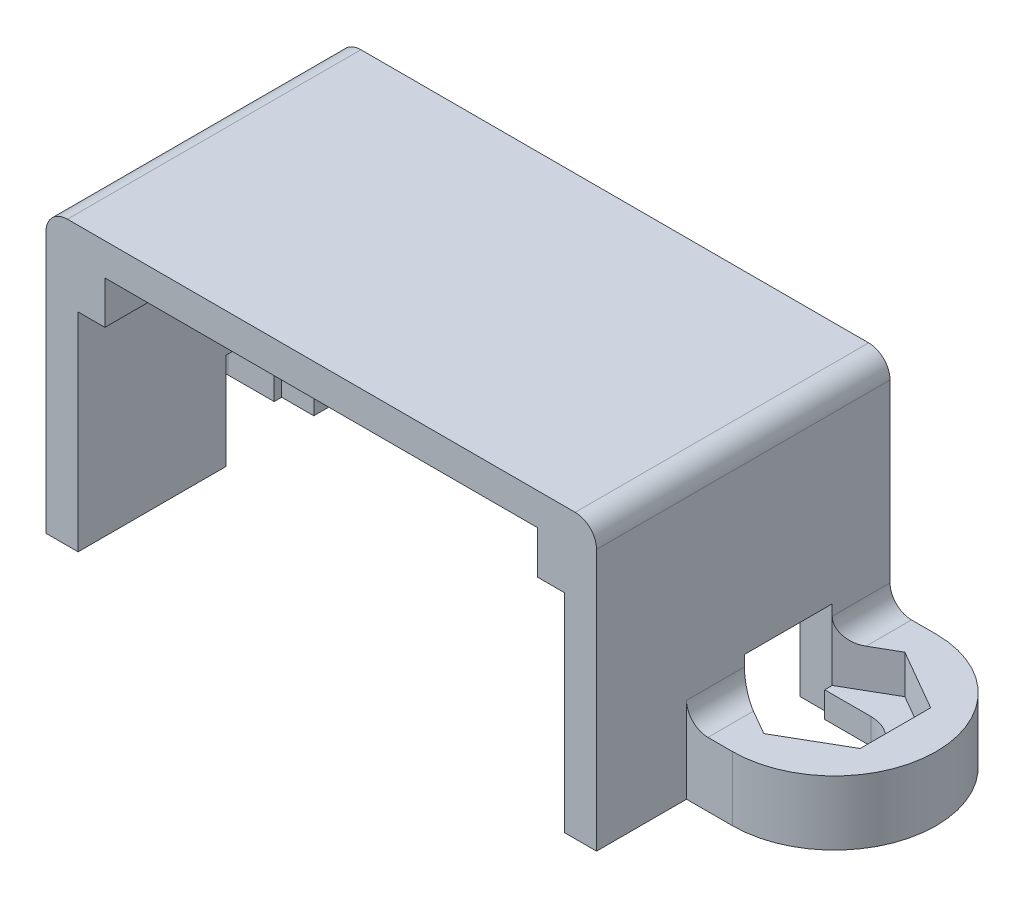
SolidWorks part; units mm, degrees
ref_plane "Front Plane" through (0, 0, 0) normal (0, 0, 1) x (1, 0, 0)
ref_plane "Top Plane" through (0, 0, 0) normal (0, 1, 0) x (1, 0, 0)
ref_plane "Right Plane" through (0, 0, 0) normal (1, 0, 0) x (0, 0, -1)
sketch "Sketch2" plane through (0, 0, 0) normal (0, 0, 1) x (1, 0, 0)
  line L1 (0, 0) -> (25.7, 0)
  line L2 (0, 0) -> (0, 13.2)
  line L3 (0, 13.2) -> (25.7, 13.2)
  line L4 (25.7, 0) -> (25.7, 13.2)
  line L5 (1.5, 0) -> (24.2, 0)
  line L6 (1.5, 0) -> (1.5, 11.7)
  line L7 (1.5, 11.7) -> (24.2, 11.7)
  line L8 (24.2, 0) -> (24.2, 11.7)
  point P9 (12.85, 0)
  point P10 (12.85, 0)
  dimension "D1" = 13.2
  dimension "D2" = 25.7
  dimension "D3" = 22.7
  dimension "D4" = 1.5
extrude "Boss-Extrude1" add sketch "Sketch2" along normal blind 13.7 contours L8 L1 L4 L3 L2 L6 L7
sketch "Sketch3" plane through (0, 0, 0) normal (0, 0, -1) x (-1, 0, 0)
  line L0 (-12.85, 13.2) -> (-12.85, 11.7) construction
  line L1 (-25.7, 0) -> (-32.6, 0)
  line L2 (-25.7, 0) -> (-25.7, 3)
  line L3 (-25.7, 3) -> (-32.6, 3)
  line L4 (-32.6, 0) -> (-32.6, 3)
  line L5 (0, 13.2) -> (-25.7, 13.2) construction
  line L6 (-1.5, 11.7) -> (-24.2, 11.7) construction
  line L7 (0, 3) -> (6.9, 3)
  line L8 (6.9, 0) -> (6.9, 3)
  line L9 (0, 0) -> (6.9, 0)
  line L10 (0, 0) -> (0, 3)
  line L11 (-24.2, 0) -> (-24.2, 11.7) construction
  dimension "D1" = 3
  dimension "D2" = 8.4
extrude "Boss-Extrude2" add sketch "Sketch3" against normal blind 9.5
sketch "Sketch4" plane through (0, 0, 0) normal (0, 0, -1) x (-1, 0, 0)
  line L0 (-12.85, 13.2) -> (-12.85, 11.7) construction
  line L1 (-24.2, 11.7) -> (-22.95, 11.7)
  line L2 (-24.2, 11.7) -> (-24.2, 9.7)
  line L3 (-24.2, 9.7) -> (-22.95, 9.7)
  line L4 (-22.95, 11.7) -> (-22.95, 9.7)
  line L5 (0, 13.2) -> (-25.7, 13.2) construction
  line L6 (-1.5, 11.7) -> (-24.2, 11.7) construction
  line L7 (-1.5, 9.7) -> (-2.75, 9.7)
  line L8 (-2.75, 11.7) -> (-2.75, 9.7)
  line L9 (-1.5, 11.7) -> (-2.75, 11.7)
  line L10 (-1.5, 11.7) -> (-1.5, 9.7)
  dimension "D1" = 2
  dimension "D2" = 1.25
extrude "Boss-Extrude3" add sketch "Sketch4" against normal up to surface (13.7 mm away) up to face at (12.85, 6.225, 13.7)
sketch "Sketch5" plane through (0, 0, 0) normal (0, 0, -1) x (-1, 0, 0)
  line L0 (-2.75, 11.7) -> (-22.95, 11.7) construction
  line L1 (-24.2, 9.7) -> (-19.8, 9.7)
  line L2 (-24.2, 9.7) -> (-24.2, 11.7)
  line L3 (-24.2, 11.7) -> (-19.8, 11.7)
  line L4 (-19.8, 9.7) -> (-19.8, 11.7)
  line L5 (-24.2, 0) -> (-24.2, 9.7) construction
  line L7 (-19.8, 9.7) -> (-22.1, 9.7)
  line L8 (-19.8, 9.7) -> (-19.8, 10.9)
  line L9 (-19.8, 10.9) -> (-22.1, 10.9)
  line L10 (-22.1, 9.7) -> (-22.1, 10.9)
  line M1 (-22.95, 11.7) -> (-2.75, 11.7)
  line M16 (-22.95, 9.7) -> (-22.95, 11.7)
  dimension "D1" = 4.4
  dimension "D2" = 2
  dimension "D3" = 2.3
  dimension "D4" = 1.2
extrude "Boss-Extrude4" add sketch "Sketch5" against normal blind 7 contours L1 L10 L9 L4 M1 M16
sketch "Sketch6" plane through (0, 3, 0) normal (0, 1, 0) x (1, 0, 0)
  line L0 (-6.9, -9.5) -> (-6.9, 0) construction
  line L1 (-6.9, -9.5) -> (0, -9.5) construction
  line L2 (-6.9, 0) -> (0, 0) construction
  line L3 (12.85, -13.7) -> (12.85, 0) construction
  line L4 (0, -13.7) -> (25.7, -13.7) construction
  line L5 (0, 0) -> (25.7, 0) construction
  line L6 (-6.9, 0) -> (-2.15, 0)
  line L7 (-6.9, -9.5) -> (-6.9, 0)
  line L8 (-6.9, -9.5) -> (-2.15, -9.5)
  line L9 (32.6, 0) -> (27.85, 0)
  line L10 (32.6, -9.5) -> (32.6, 0)
  line L11 (32.6, -9.5) -> (27.85, -9.5)
  arc A0 (-2.15, 0) -> (-2.15, -9.5) centre (-2.15, -4.75) ccw
  arc A1 (27.85, 0) -> (27.85, -9.5) centre (27.85, -4.75) cw
  line M6 (0, 0) -> (-6.9, 0)
  line M7 (-6.9, 0) -> (-6.9, -9.5)
  line M8 (-6.9, -9.5) -> (0, -9.5)
extrude "Cut-Extrude1" cut sketch "Sketch6" against normal through all contours L10 A1 L11 | L9 A1 L10 | A0 M6 M7 | A0 L7 M8
sketch "Sketch7" plane through (0, 3, 0) normal (0, 1, 0) x (1, 0, 0)
  line L1 (12.85, -13.7) -> (12.85, 0) construction
  line L2 (0, -13.7) -> (25.7, -13.7) construction
  line L3 (0, 0) -> (25.7, 0) construction
  line L4 (-2.15, -6.45) -> (3.2434, -6.45)
  line L5 (-2.15, -6.45) -> (-2.15, -3.05)
  line L6 (-2.15, -3.05) -> (3.2434, -3.05)
  line L7 (3.2434, -6.45) -> (3.2434, -3.05)
  arc A0 (-2.15, -3.05) -> (-2.15, -6.45) centre (-2.15, -4.75) ccw
  circle A1 centre (27.85, -4.75) radius 1.7
  point P0 (-2.15, -4.75)
  line M5 (0, -9.5) -> (0, 0)
  dimension "D1" = 15
extrude "Cut-Extrude2" cut sketch "Sketch7" against normal through all contours L6 L5 L4 M5 | L5 A0
sketch "Sketch8" plane through (0, 3, 0) normal (0, 1, 0) x (1, 0, 0)
  line L0 (12.85, -13.7) -> (12.85, 0) construction
  line L1 (-2.15, -8.0409) -> (0.7, -6.3954)
  line L2 (0.7, -6.3954) -> (0.7, -3.1046)
  line L3 (0.7, -3.1046) -> (-2.15, -1.4591)
  line L4 (-2.15, -1.4591) -> (-5, -3.1046)
  line L5 (-5, -3.1046) -> (-5, -6.3954)
  line L6 (-5, -6.3954) -> (-2.15, -8.0409)
  line L7 (0, -13.7) -> (25.7, -13.7) construction
  line L8 (0, 0) -> (25.7, 0) construction
  line L9 (30.7, -6.3954) -> (27.85, -8.0409)
  line L10 (30.7, -3.1046) -> (30.7, -6.3954)
  line L11 (27.85, -1.4591) -> (30.7, -3.1046)
  line L12 (25, -3.1046) -> (27.85, -1.4591)
  line L13 (25, -6.3954) -> (25, -3.1046)
  line L14 (27.85, -8.0409) -> (25, -6.3954)
  circle A0 centre (-2.15, -4.75) radius 2.85 construction
  point P0 (-2.15, -4.75)
  dimension "D1" = 5.7
extrude "Cut-Extrude3" cut sketch "Sketch8" against normal blind 1.8
sketch "Sketch9" plane through (1.5, 0, 0) normal (1, 0, 0) x (0, 0, -1)
  line L0 (-13.7, 0) -> (0, 0) construction
  line L1 (-6.7996, 0) -> (-2.7004, 0)
  line L2 (-6.7996, 0) -> (-6.7996, 4.5)
  line L3 (-6.7996, 4.5) -> (-2.7004, 4.5)
  line L4 (-2.7004, 0) -> (-2.7004, 4.5)
  dimension "D3" = 4.5
extrude "Cut-Extrude4" cut sketch "Sketch9" against normal up to surface (1.5 mm away) up to face at (0, 4.8, 6.9875)
fillet "Fillet1" radius 1 4 edges at (25.7, 3, 8.1498) (25.7, 3, 1.3502) (0, 3, 1.3502) (0, 3, 8.1498)
ref_plane "Plane4" through (12.85, 0, 0) normal (1, 0, 0) x (0, 0, -1)
mirror "Mirror1" about plane through (12.85, 0, 0) normal (1, 0, 0) of "Cut-Extrude4", "Cut-Extrude3", "Cut-Extrude2"
fillet "Fillet2" radius 1 2 edges at (25.7, 13.2, 6.85) (0, 13.2, 6.85)
